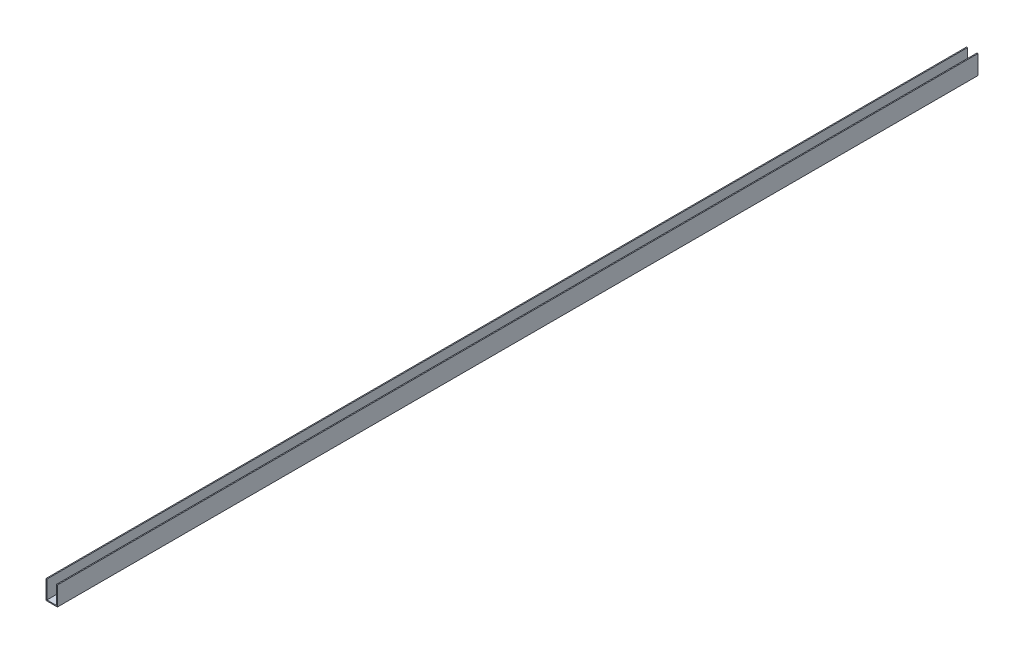
SolidWorks part; units mm, degrees
material "6061 合金"
ref_plane "前视基准面" through (0, 0, 0) normal (0, 0, 1) x (1, 0, 0)
ref_plane "上视基准面" through (0, 0, 0) normal (0, 1, 0) x (1, 0, 0)
ref_plane "右视基准面" through (0, 0, 0) normal (1, 0, 0) x (0, 0, -1)
sketch "草图1" plane through (0, 0, 0) normal (0, 0, 1) x (1, 0, 0)
  line L0 (-2.61, 5.025) -> (-3.16, 5.025)
  line L1 (2.61, -5.025) -> (-2.61, -5.025)
  line L2 (2.61, -5.025) -> (2.61, 5.025)
  line L3 (2.61, 5.025) -> (-2.61, 5.025) construction
  line L4 (-2.61, -5.025) -> (-2.61, 5.025)
  line L5 (2.61, -5.025) -> (-2.61, 5.025) construction
  line L6 (2.61, 5.025) -> (-2.61, -5.025) construction
  line L7 (-3.16, 5.025) -> (-3.16, -5.575)
  line L8 (-3.16, -5.575) -> (3.16, -5.575)
  line L9 (3.16, -5.575) -> (3.16, 5.025)
  line L10 (3.16, 5.025) -> (2.61, 5.025)
  point P0 (0, 0)
  dimension "D1" = 0.55
  dimension "D2" = 10.6
  dimension "D3" = 0.55
  dimension "D4" = 6.32
extrude "凸台-拉伸1" add sketch "草图1" along normal blind 511
